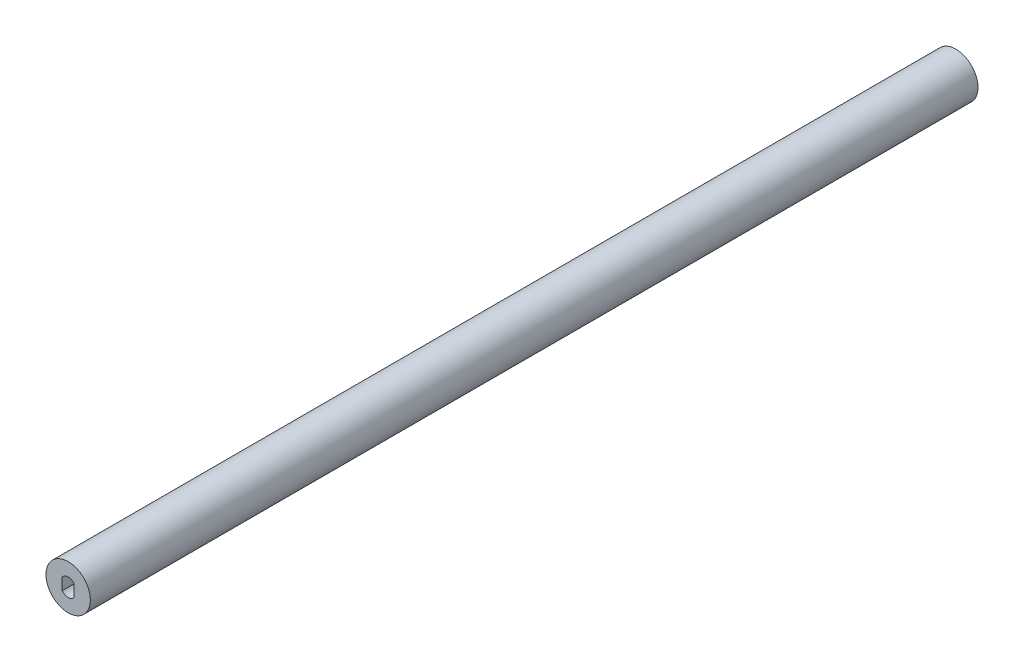
SolidWorks part; units mm, degrees
ref_plane "Front Plane" through (0, 0, 0) normal (0, 0, 1) x (1, 0, 0)
ref_plane "Top Plane" through (0, 0, 0) normal (0, 1, 0) x (1, 0, 0)
ref_plane "Right Plane" through (0, 0, 0) normal (1, 0, 0) x (0, 0, -1)
sketch "Sketch1" plane through (0, 0, 0) normal (0, 0, 1) x (1, 0, 0)
  circle A0 centre (-21.9281, 1.412) radius 7.5
  dimension "D1" = 15
extrude "Boss-Extrude1" add sketch "Sketch1" along normal blind 300
sketch "Sketch2" plane through (0, 0, 300) normal (0, 0, 1) x (1, 0, 0)
  line L0 (-21.9281, 8.912) -> (-21.9281, -6.088) construction
  line L1 (-29.4281, 1.412) -> (-14.4281, 1.412) construction
  line L4 (-23.9281, 3.412) -> (-23.9281, -0.588)
  line L6 (-19.9281, 3.412) -> (-19.9281, -0.588)
  line L7 (-23.9281, 3.412) -> (-19.9281, -0.588) construction
  line L8 (-23.9281, -0.588) -> (-19.9281, 3.412) construction
  circle A0 centre (-21.9281, 1.412) radius 7.5 construction
  arc A1 (-23.9281, 3.412) -> (-19.9281, 3.412) centre (-21.9281, 1.912) cw
  arc A2 (-23.9281, -0.588) -> (-19.9281, -0.588) centre (-21.9281, 0.912) ccw
  point P7 (-21.9281, 1.412)
  dimension "D3" = 2.5
  dimension "D1" = 4
  dimension "D2" = 4
extrude "Cut-Extrude1" cut sketch "Sketch2" against normal blind 5
